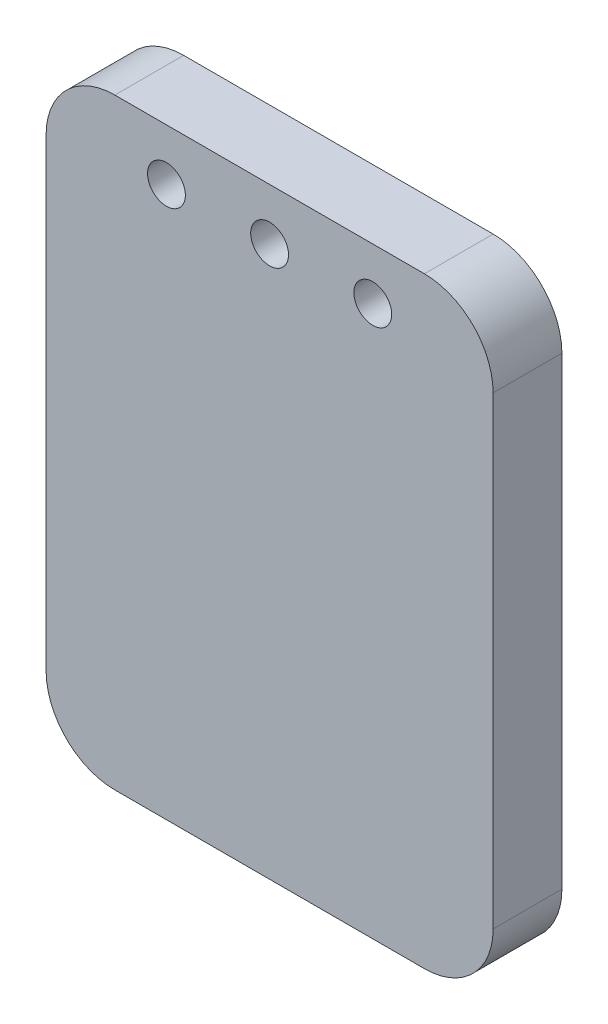
SolidWorks part; units mm, degrees
ref_plane "Front" through (0, 0, 0) normal (0, 0, 1) x (1, 0, 0)
ref_plane "Top" through (0, 0, 0) normal (0, 1, 0) x (1, 0, 0)
ref_plane "Right" through (0, 0, 0) normal (1, 0, 0) x (0, 0, -1)
sketch "Sketch1" plane through (0, 0, 0) normal (0, 0, 1) x (1, 0, 0)
  line L1 (-32.5, 43.75) -> (32.5, 43.75)
  line L2 (-32.5, 43.75) -> (-32.5, -43.75)
  line L3 (-32.5, -43.75) -> (32.5, -43.75)
  line L4 (32.5, 43.75) -> (32.5, -43.75)
  line L5 (-32.5, 43.75) -> (32.5, -43.75) construction
  line L6 (-32.5, -43.75) -> (32.5, 43.75) construction
  circle A0 centre (-15, 36.25) radius 2.75
  circle A1 centre (0, 36.25) radius 2.75
  circle A2 centre (15, 36.25) radius 2.75
  point P4 (0, 0)
  dimension "D3" = 15
  dimension "D4" = 15
  dimension "D5" = 5.5
  dimension "D1" = 87.5
  dimension "D2" = 65
  dimension "D6" = 7.5
extrude "Boss-Extrude1" add sketch "Sketch1" along normal blind 10
fillet "Fillet1" radius 10 4 edges at (-32.5, 43.75, 5) (32.5, 43.75, 5) (32.5, -43.75, 5) (-32.5, -43.75, 5)
